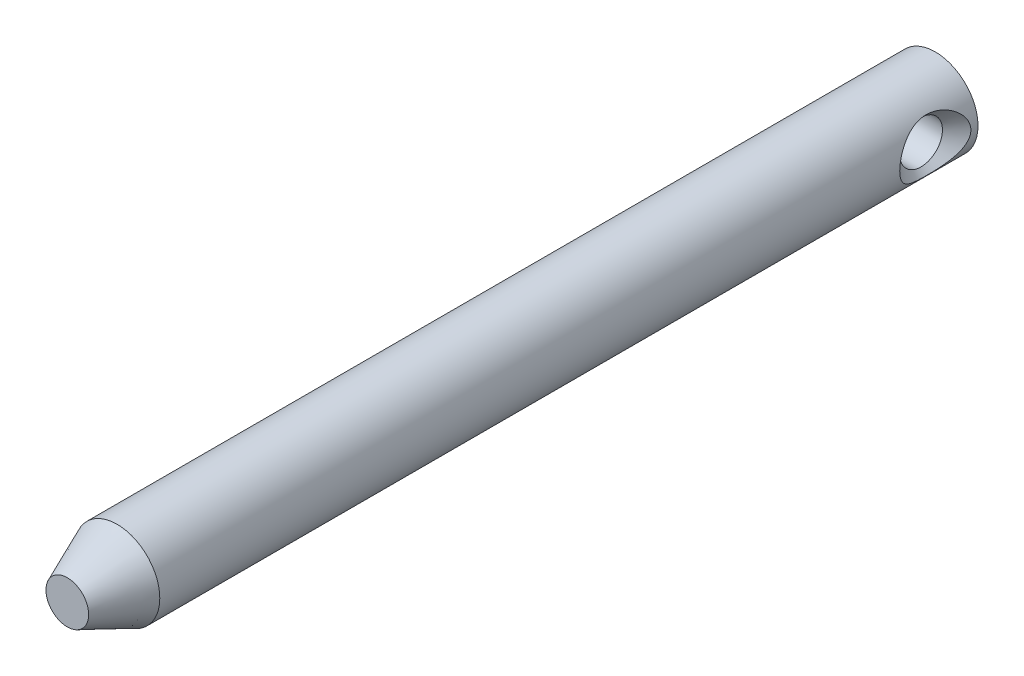
SolidWorks part; units mm, degrees
material "3.3535 (EN-AW 5754)"
ref_plane "Front" through (0, 0, 0) normal (0, 0, 1) x (1, 0, 0)
ref_plane "Top" through (0, 0, 0) normal (0, 1, 0) x (1, 0, 0)
ref_plane "Right" through (0, 0, 0) normal (1, 0, 0) x (0, 0, -1)
sketch "Esquisse1" plane through (0, 0, 0) normal (0, 0, 1) x (1, 0, 0)
  circle A0 centre (0, 0) radius 3
  dimension "D1" = 6
extrude "Boss.-Extru.1" add sketch "Esquisse1" along normal blind 61 from offset 3 offset against normal yes
chamfer "Chanfrein1" distance 3.5 distance2 1.5 1 edges at (3, 0, 58)
sketch "Esquisse2" plane through (0, 0, 0) normal (0, 1, 0) x (1, 0, 0)
  line L0 (-3, 0) -> (3, 0)
  line L1 (3, 0) -> (3, 2.5)
  line L2 (3, 2.5) -> (2, 1.5)
  line L3 (2, 1.5) -> (-2, 1.5)
  line L4 (0, 1.5) -> (0, 0) construction
  line L5 (-3, 2.5) -> (-2, 1.5)
  line L6 (-3, 0) -> (-3, 2.5)
  line L7 (3, -54.5) -> (3, 3) construction
  line L8 (-3, 0) -> (-5.5, 0) construction
  dimension "D1" = 45
  dimension "D2" = 1
  dimension "D3" = 3
revolve "Enlèvement de matière-Révolution1" cut sketch "Esquisse2" angle 360 about L8
